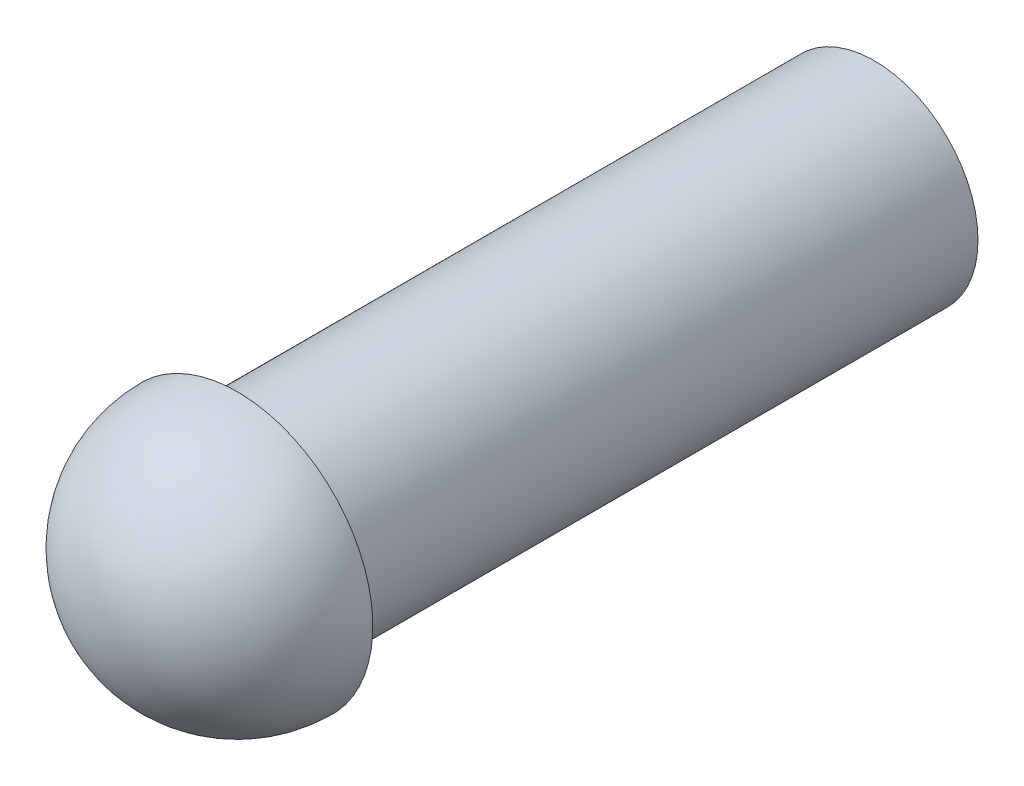
SolidWorks part; units mm, degrees
ref_plane "Plan de face" through (0, 0, 0) normal (0, 0, 1) x (1, 0, 0)
ref_plane "Plan de dessus" through (0, 0, 0) normal (0, 1, 0) x (1, 0, 0)
ref_plane "Plan de droite" through (0, 0, 0) normal (1, 0, 0) x (0, 0, -1)
sketch "Esquisse1" plane through (0, 0, 0) normal (0, 0, 1) x (1, 0, 0)
  circle A0 centre (0, 0) radius 3.25
  dimension "D1" = 6.5
extrude "Boss.-Extru.1" add sketch "Esquisse1" along normal blind 20
sketch "Esquisse2" plane through (0, 0, 20) normal (0, 0, 1) x (1, 0, 0)
  line L0 (0, -4.25) -> (0, 4.25)
  arc A0 (0, 4.25) -> (0, -4.25) centre (0, 0) ccw
  dimension "D1" = 8.5
revolve "Révolution1" add sketch "Esquisse2" angle 180 about L0
